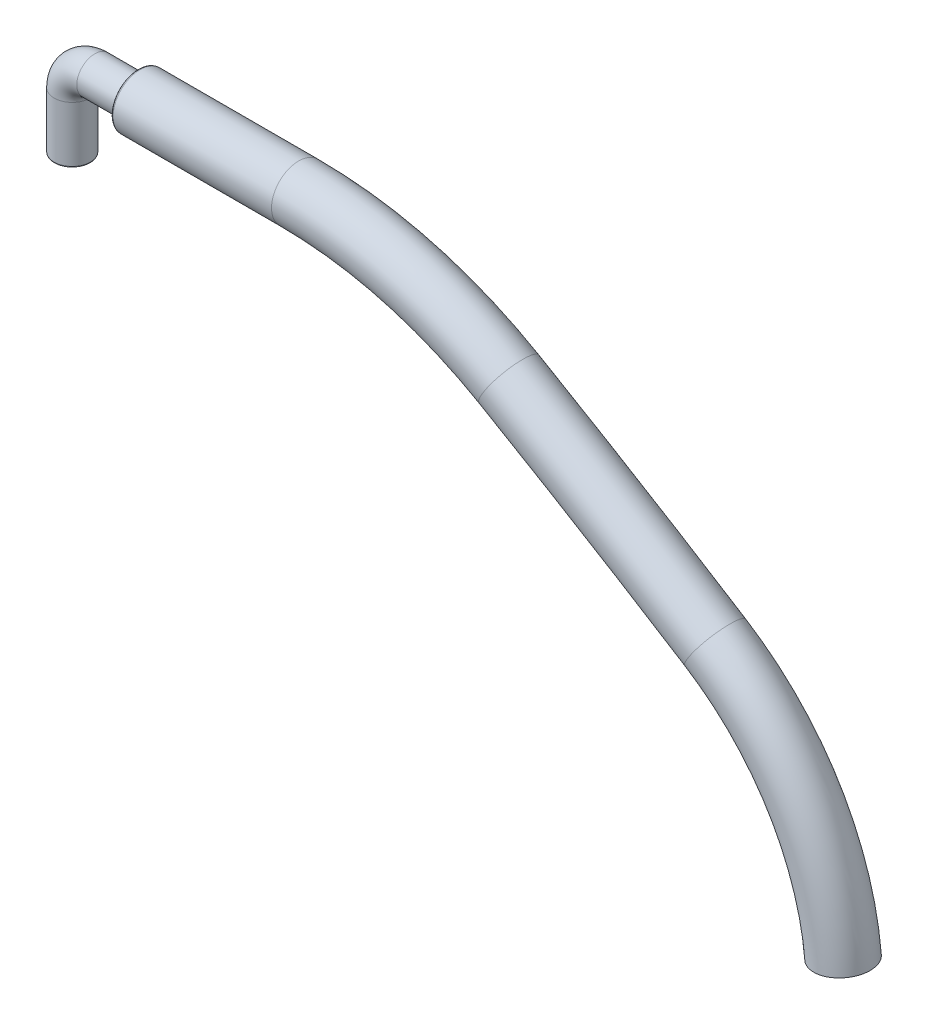
SolidWorks part; units mm, degrees
ref_plane "Alzado" through (0, 0, 0) normal (0, 0, 1) x (1, 0, 0)
ref_plane "Planta" through (0, 0, 0) normal (0, 1, 0) x (1, 0, 0)
ref_plane "Vista lateral" through (0, 0, 0) normal (1, 0, 0) x (0, 0, -1)
sketch "Croquis1" plane through (0, 0, 0) normal (0, 0, 1) x (1, 0, 0)
  line L0 (0, -10) -> (0, -35)
  line L1 (10, 0) -> (50, 0)
  line L2 (0, -10) -> (23.5725, -10) construction
  line L3 (50, 0) -> (50, 2.9617) construction
  line L4 (50, 0) -> (53.7086, 0) construction
  line L5 (16, 0) -> (16, 26.592) construction
  line L6 (0, -31) -> (18.2487, -31) construction
  line L7 (46, 0) -> (46, 28.3563) construction
  line L8 (0, -11) -> (26.2947, -11) construction
  arc A0 (0, -10) -> (10, 0) centre (10, -10) cw
  point P6 (0, 0)
  dimension "D1" = 10
  dimension "D2" = 25
  dimension "D3" = 40
  dimension "D4" = 4
  dimension "D5" = 30
  dimension "D6" = 4
  dimension "D7" = 20
ref_plane "Plano1" through (0, -35, 0) normal (0, -1, 0) x (1, 0, 0)
sketch "Croquis2" plane through (0, -35, 0) normal (0, -1, 0) x (1, 0, 0)
  line L0 (0, 0) -> (0, -10.1083) construction
  line L1 (0, 0) -> (-12.2077, 0) construction
  circle A0 centre (0, 0) radius 8
  dimension "D1" = 16
sweep "Barrer1" add profiles "Croquis2" path "Croquis1"
shell "Vaciado2" thickness 2
fillet "Redondeo1" radius 0.5 4 edges at (6, -35, 0) (8, -35, 0) (50, -8, 0) (50, -6, 0)
sketch "Croquis3" plane through (0, -35, 0) normal (0, -1, 0) x (1, 0, 0)
  line L0 (0, 0) -> (10.9751, 0) construction
  line L1 (0, 0) -> (0, -13.0055) construction
sketch "Croquis5" plane through (50, 0, 0) normal (1, 0, 0) x (0, 0, -1)
  line L0 (0, 0) -> (12.3974, 0) construction
sketch "Croquis6" plane through (0, 0, 0) normal (0, 0, 1) x (1, 0, 0)
  line L0 (29.0946, 0) -> (100.1574, 0)
  arc A0 (100.1574, 0) -> (193.1068, -24.9738) centre (100.1574, -185.4602) cw
  arc A1 (193.1068, -24.9738) -> (284.383, -80.234) centre (-1183.228, -2401.3522) cw
  arc A2 (284.383, -80.234) -> (340.9628, -172.8191) centre (218.8662, -183.8529) cw
ref_plane "Plano2" through (29.0946, 0, 0) normal (1, 0, 0) x (0, 0, -1)
sketch "Croquis7" plane through (29.0946, 0, 0) normal (1, 0, 0) x (0, 0, -1)
  circle A0 centre (0, 0) radius 12
  dimension "D1" = 24
sweep "Barrer2" add profiles "Croquis7" path "Croquis6"
shell "Vaciado3" thickness 4
fillet "Redondeo2" radius 1 1 edges at (29.0946, 0, -12)
